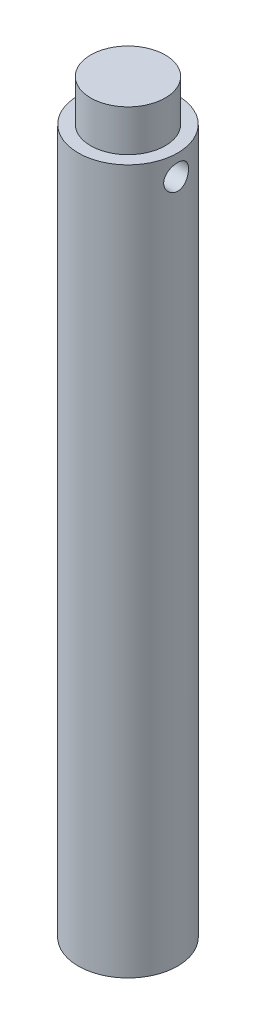
SolidWorks part; units mm, degrees
material "AISI 1015 Сталь, холоднотянутая (SS)"
ref_plane "Спереди (XY)" through (0, 0, 0) normal (0, 0, 1) x (1, 0, 0)
ref_plane "Сверху (XZ)" through (0, 0, 0) normal (0, 1, 0) x (1, 0, 0)
ref_plane "Справа (ZY)" through (0, 0, 0) normal (1, 0, 0) x (0, 0, -1)
sketch "Эскиз1" plane through (0, 0, 0) normal (0, 1, 0) x (1, 0, 0)
  circle A0 centre (0, 0) radius 6
  circle A1 centre (0, 0) radius 4.5
  dimension "D1" = 12
  dimension "D2" = 9
extrude "Бобышка-Вытянуть1" add sketch "Эскиз1" against normal blind 80 contours A0
sketch "Эскиз2" plane through (0, 0, 0) normal (0, 1, 0) x (1, 0, 0)
  circle A0 centre (0, 0) radius 4.5
  dimension "D1" = 9
extrude "Бобышка-Вытянуть2" add sketch "Эскиз2" along normal blind 10
sketch "Эскиз3" plane through (0, 0, 0) normal (0, 1, 0) x (1, 0, 0)
  circle A0 centre (0, 0) radius 6 construction
  circle A1 centre (0, 0) radius 6
extrude "Бобышка-Вытянуть3" add sketch "Эскиз3" along normal blind 5
sketch "Эскиз4" plane through (0, 0, 0) normal (1, 0, 0) x (0, 0, -1)
  line L0 (6, 5) -> (-6, 5) construction
  circle A0 centre (0, 2.5) radius 1.5
  dimension "D1" = 3
  dimension "D2" = 2.5
extrude "Вырез-Вытянуть1" cut sketch "Эскиз4" against normal through all both and the other way through all
